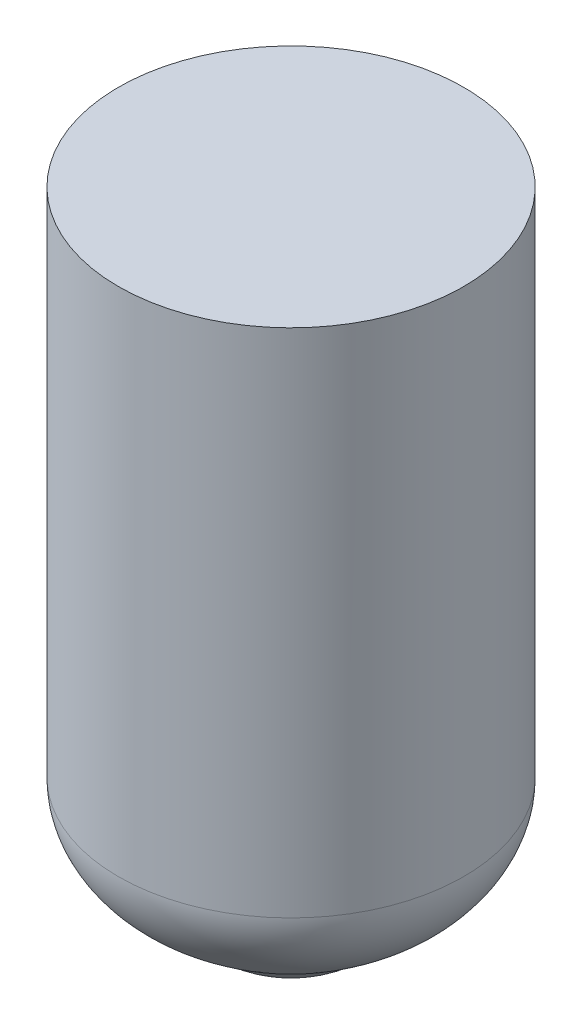
SolidWorks part; units mm, degrees
material "Ductile Iron"
ref_plane "Front Plane" through (0, 0, 0) normal (0, 0, 1) x (1, 0, 0)
ref_plane "Top Plane" through (0, 0, 0) normal (0, 1, 0) x (1, 0, 0)
ref_plane "Right Plane" through (0, 0, 0) normal (1, 0, 0) x (0, 0, -1)
sketch "Sketch1" plane through (0, 0, 0) normal (0, 0, 1) x (1, 0, 0)
  line L0 (0, 0) -> (0, 135.3473) construction
  line L1 (-30.4, 25) -> (-30.4, 115)
  line L2 (-30.4, 115) -> (0, 115)
  line L3 (0, 0) -> (-66.6972, 0) construction
  line L4 (0, 115) -> (0, 0)
  spline S0 degree 3 poles (0, 0) (-10.5315, 0) (-12.5384, 4.7606) (-26.1028, 12.4147) (-30.4, 20.5203) (-30.4, 25) knots 0 0 0 0 0.388265 0.683336 1 1 1 1
  dimension "D3" = 25
  dimension "D1" = 90
  dimension "D2" = 30.4
revolve "Revolve1" add sketch "Sketch1" angle 360 about L4
